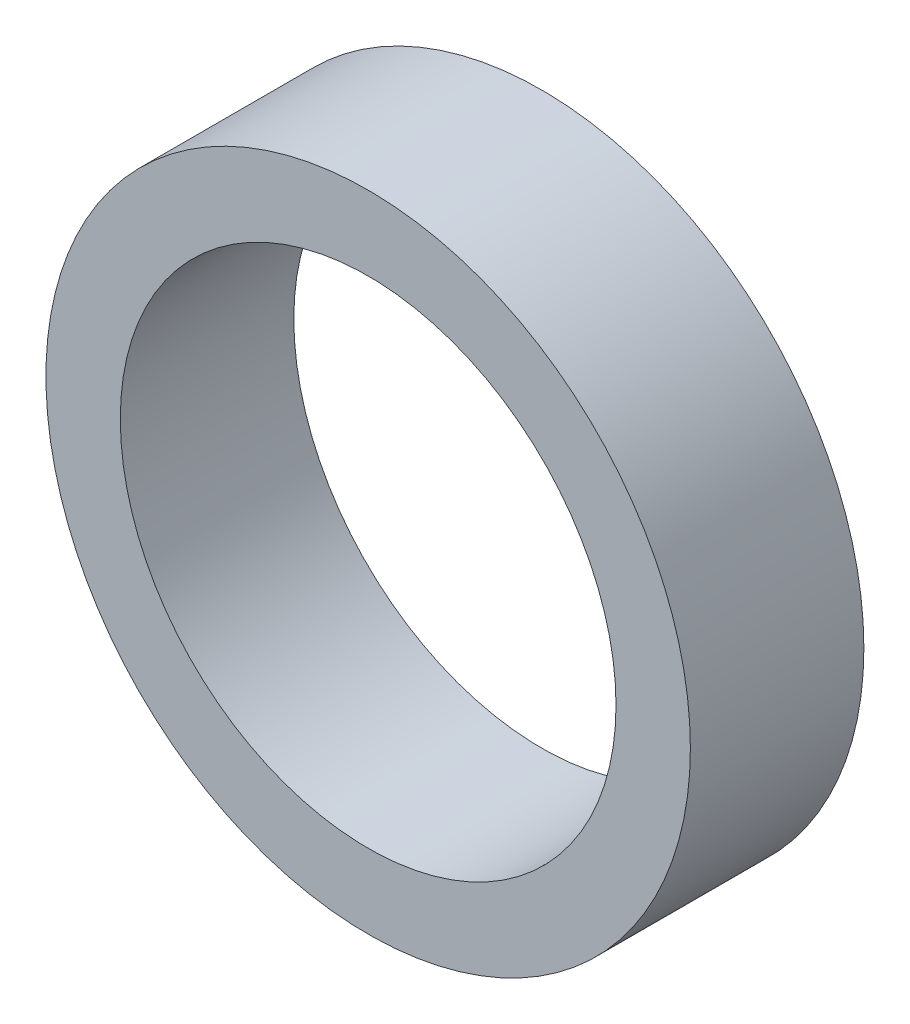
SolidWorks part; units mm, degrees
ref_plane "Front Plane" through (0, 0, 0) normal (0, 0, 1) x (1, 0, 0)
ref_plane "Top Plane" through (0, 0, 0) normal (0, 1, 0) x (1, 0, 0)
ref_plane "Right Plane" through (0, 0, 0) normal (1, 0, 0) x (0, 0, -1)
sketch "Sketch1" plane through (0, 0, 0) normal (0, 0, 1) x (1, 0, 0)
  circle A0 centre (0, 0) radius 6.5
  dimension "D1" = 13
extrude "Boss-Extrude1" add sketch "Sketch1" along normal blind 3.5
sketch "Sketch5" plane through (0, 0, 3.5) normal (0, 0, 1) x (1, 0, 0)
  circle A0 centre (0, 0) radius 5
  dimension "D1" = 10
extrude "Cut-Extrude3" cut sketch "Sketch5" against normal blind 3.5 contours A0
